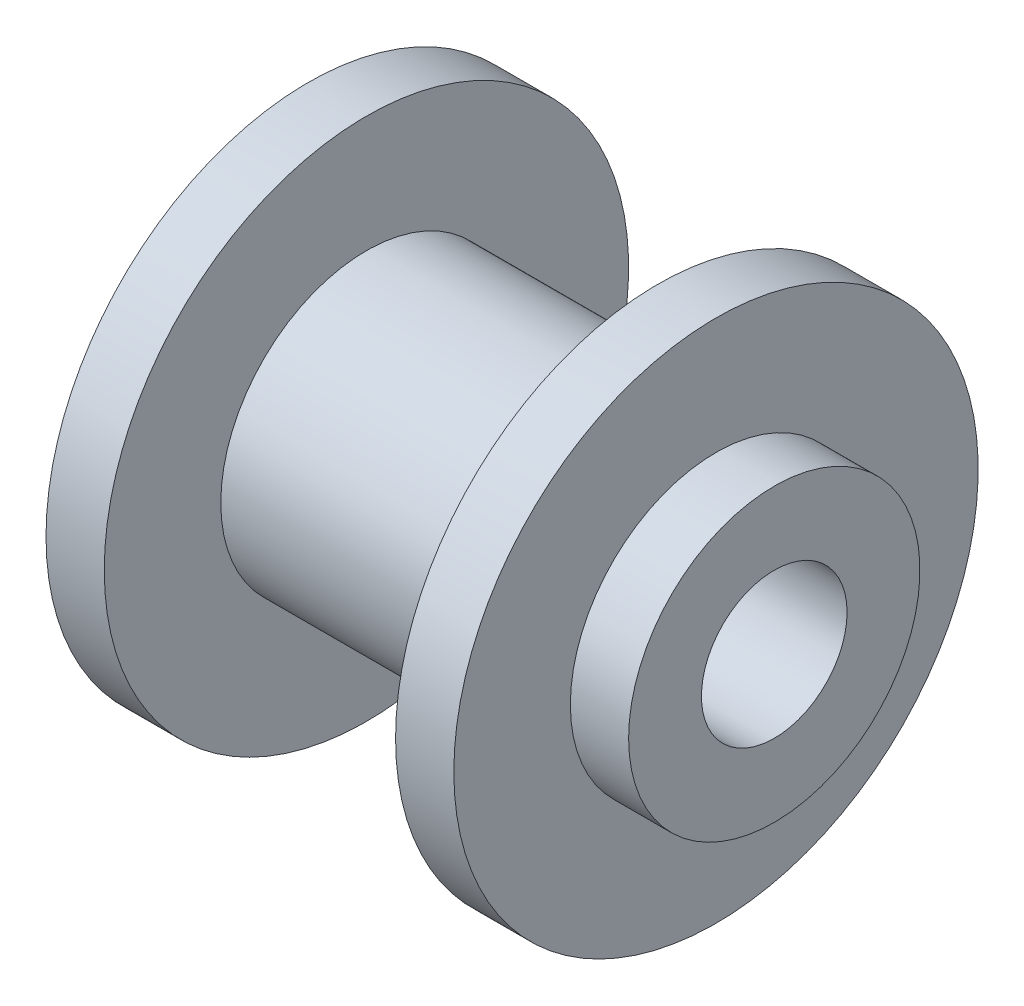
SolidWorks part; units mm, degrees
ref_plane "Front Plane" through (0, 0, 0) normal (0, 0, 1) x (1, 0, 0)
ref_plane "Top Plane" through (0, 0, 0) normal (0, 1, 0) x (1, 0, 0)
ref_plane "Right Plane" through (0, 0, 0) normal (1, 0, 0) x (0, 0, -1)
sketch "Sketch1" plane through (0, 0, 0) normal (0, 0, 1) x (1, 0, 0)
  line L0 (0, 0) -> (0, 5)
  line L1 (0, 5) -> (2, 5)
  line L2 (2, 5) -> (2, 9)
  line L3 (2, 9) -> (4, 9)
  line L4 (4, 9) -> (4, 5)
  line L5 (4, 5) -> (14, 5)
  line L6 (14, 5) -> (14, 9)
  line L7 (14, 9) -> (16, 9)
  line L8 (16, 9) -> (16, 5)
  line L9 (16, 5) -> (18, 5)
  line L10 (18, 5) -> (18, 0)
  line L11 (0, 0) -> (27.3418, 0) construction
  line L12 (0, 0) -> (18, 0)
  dimension "D1" = 5
  dimension "D2" = 2
  dimension "D3" = 4
  dimension "D4" = 2
  dimension "D5" = 10
revolve "Revolve1" add sketch "Sketch1" angle 360 about L11
sketch "Sketch2" plane through (18, 0, 0) normal (1, 0, 0) x (0, 0, -1)
  circle A0 centre (0, 0) radius 2.5
  dimension "D1" = 5
extrude "Cut-Extrude1" cut sketch "Sketch2" against normal through all
